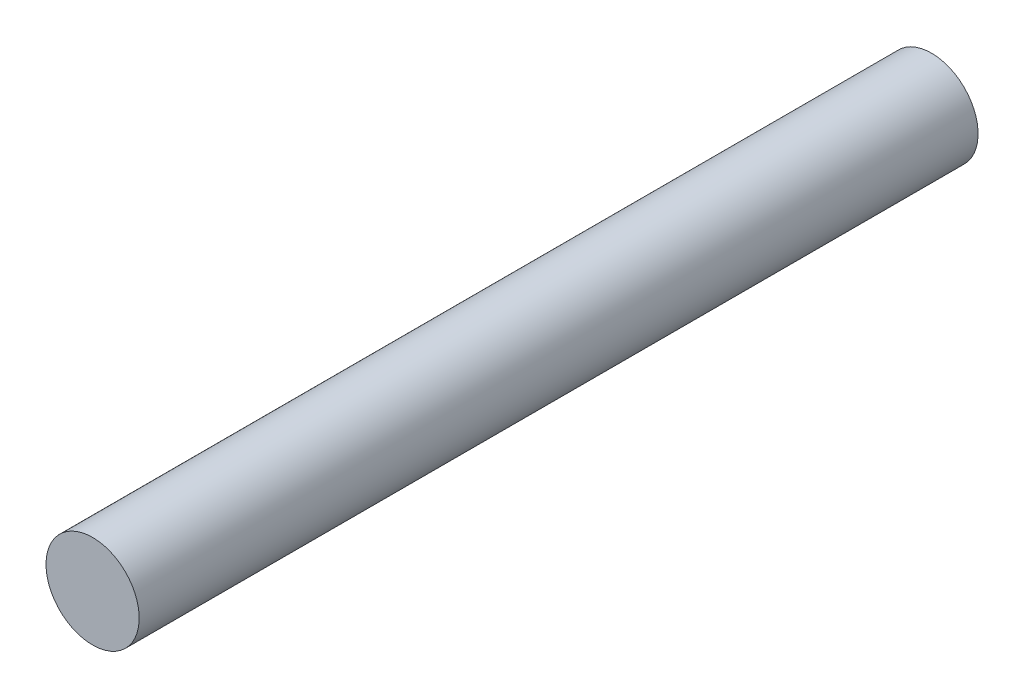
SolidWorks part; units mm, degrees
ref_plane "Front Plane" through (0, 0, 0) normal (0, 0, 1) x (1, 0, 0)
ref_plane "Top Plane" through (0, 0, 0) normal (0, 1, 0) x (1, 0, 0)
ref_plane "Right Plane" through (0, 0, 0) normal (1, 0, 0) x (0, 0, -1)
sketch "Sketch2" plane through (0, 0, 0) normal (0, 0, 1) x (1, 0, 0)
  circle A0 centre (3.1256, 22.5533) radius 2.5
  dimension "D1" = 5
extrude "Boss-Extrude1" add sketch "Sketch2" along normal blind 45
